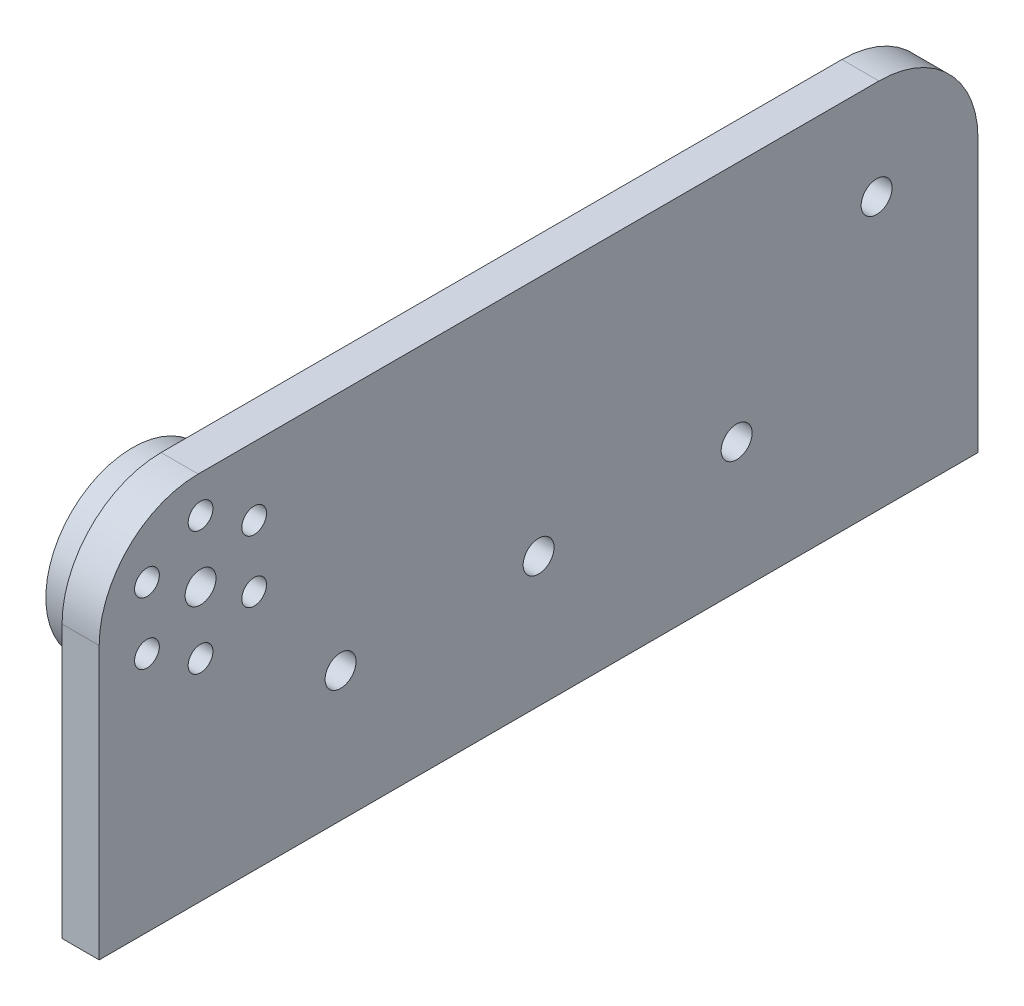
SolidWorks part; units mm, degrees
ref_plane "Front Plane" through (0, 0, 0) normal (0, 0, 1) x (1, 0, 0)
ref_plane "Top Plane" through (0, 0, 0) normal (0, 1, 0) x (1, 0, 0)
ref_plane "Right Plane" through (0, 0, 0) normal (1, 0, 0) x (0, 0, -1)
sketch "Sketch1" plane through (0, 0, 0) normal (1, 0, 0) x (0, 0, -1)
  line L1 (35.5, -15) -> (-35.5, -15)
  line L2 (35.5, -15) -> (35.5, 15)
  line L3 (35.5, 15) -> (-35.5, 15)
  line L4 (-35.5, -15) -> (-35.5, 15)
  line L5 (35.5, -15) -> (-35.5, 15) construction
  line L6 (35.5, 15) -> (-35.5, -15) construction
  point P0 (0, 0)
  dimension "D1" = 71
  dimension "D2" = 30
extrude "Boss-Extrude1" add sketch "Sketch1" along normal blind 3
sketch "Sketch2" plane through (3, 0, 0) normal (1, 0, 0) x (0, 0, -1)
  line L3 (-35.5, -15) -> (35.5, -15) construction
  circle A0 centre (-27.31, 7) radius 1.25
  circle A5 centre (0, -4.5) radius 1.25
  circle A7 centre (-16, -4.5) radius 1.25
  point P6 (0, 0)
  point P7 (0, 0)
  dimension "D3" = 2.5
  dimension "D4" = 2.5
  dimension "D5" = 10.5
  dimension "D6" = 2.5
  dimension "D1" = 22
  dimension "D2" = 27.31
  dimension "D7" = 10.5
  dimension "D8" = 16
extrude "Cut-Extrude1" cut sketch "Sketch2" against normal blind 5
mirror "Mirror1" about plane through (0, 0, 0) normal (0, 0, 1) of "Cut-Extrude1"
fillet "Fillet1" radius 8 2 edges at (1.5, 15, -35.5) (1.5, 15, 35.5)
sketch "Sketch3" plane through (0, 0, 0) normal (1, 0, 0) x (0, 0, -1)
  circle A0 centre (-27.31, 7) radius 7
  circle A1 centre (-27.31, 7) radius 1.25
  dimension "D1" = 14
extrude "Boss-Extrude2" add sketch "Sketch3" against normal blind 2.5
sketch "Sketch4" plane through (-2.5, 0, 0) normal (-1, 0, 0) x (0, 0, 1)
  circle A0 centre (27.31, 7) radius 5
  circle A1 centre (27.31, 12) radius 1
  dimension "D1" = 10
  dimension "D2" = 2
extrude "Cut-Extrude2" cut sketch "Sketch4" against normal blind 10 contours A0 A1 | A0 A1
pattern_circular "CirPattern1" count 6 every 60 about axis through (0, 7, 27.31) along (1, 0, 0) of "Cut-Extrude2"
